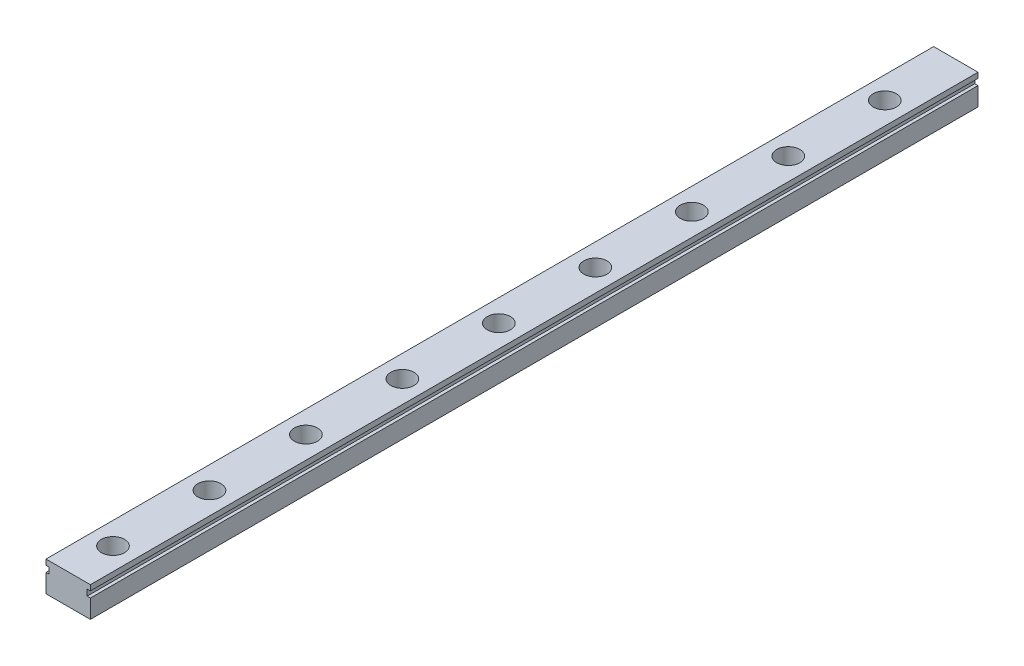
SolidWorks part; units mm, degrees
ref_plane "Front Plane" through (0, 0, 0) normal (0, 0, 1) x (1, 0, 0)
ref_plane "Top Plane" through (0, 0, 0) normal (0, 1, 0) x (1, 0, 0)
ref_plane "Right Plane" through (0, 0, 0) normal (1, 0, 0) x (0, 0, -1)
sketch "Sketch1" plane through (0, 0, 0) normal (0, 0, 1) x (1, 0, 0)
  line L1 (-5.75, -3.9) -> (5.75, -3.9)
  line L2 (-5.75, -3.9) -> (-5.75, 3.9)
  line L3 (-5.75, 3.9) -> (5.75, 3.9)
  line L4 (5.75, -3.9) -> (5.75, 3.9)
  line L5 (-5.75, -3.9) -> (5.75, 3.9) construction
  line L6 (-5.75, 3.9) -> (5.75, -3.9) construction
  point P0 (0, 0)
  dimension "D1" = 11.5
  dimension "D2" = 7.8
extrude "Boss-Extrude1" add sketch "Sketch1" along normal blind 230
sketch "Sketch2" plane through (0, 0, 230) normal (0, 0, 1) x (1, 0, 0)
  line L0 (5.75, -3.9) -> (5.75, 3.9) construction
  line L1 (5.75, 2.5) -> (4.9147, 2.5)
  line L2 (5.75, 2.5) -> (5.75, 0.9)
  line L3 (5.75, 0.9) -> (4.9147, 0.9)
  line L4 (4.9147, 2.5) -> (4.9147, 0.9)
  line L5 (5.75, 3.9) -> (-5.75, 3.9) construction
  line L7 (0, -55) -> (0, 55) construction
  line L8 (-5.75, 0.9) -> (-4.9147, 0.9)
  line L9 (-4.9147, 2.5) -> (-4.9147, 0.9)
  line L10 (-5.75, 2.5) -> (-4.9147, 2.5)
  line L11 (-5.75, 2.5) -> (-5.75, 0.9)
  dimension "D1" = 1.4
  dimension "D2" = 1.6
extrude "Cut-Extrude1" cut sketch "Sketch2" against normal through all
sketch "Sketch3" plane through (0, 3.9, 0) normal (0, 1, 0) x (1, 0, 0)
  line L0 (0, -223.2) -> (0, -215.9183) construction
  line L2 (5.75, -230) -> (-5.75, -230) construction
  circle A0 centre (0, -218.4) radius 3
  circle A1 centre (0, -193.4) radius 3
  circle A2 centre (0, -168.4) radius 3
  circle A3 centre (0, -143.4) radius 3
  circle A4 centre (0, -118.4) radius 3
  circle A5 centre (0, -93.4) radius 3
  circle A6 centre (0, -68.4) radius 3
  circle A7 centre (0, -43.4) radius 3
  circle A8 centre (0, -18.4) radius 3
  circle A9 centre (0, 6.6) radius 3
  circle A10 centre (0, 31.6) radius 3
  circle A11 centre (0, 56.6) radius 3
  circle A12 centre (0, 81.6) radius 3
  circle A13 centre (0, 106.6) radius 3
  circle A14 centre (0, 131.6) radius 3
  circle A15 centre (0, 156.6) radius 3
  circle A16 centre (0, 181.6) radius 3
  circle A17 centre (0, 206.6) radius 3
  circle A18 centre (0, 231.6) radius 3
  circle A19 centre (0, 256.6) radius 3
  circle A20 centre (0, 281.6) radius 3
  circle A21 centre (0, 306.6) radius 3
  circle A22 centre (0, 331.6) radius 3
  circle A23 centre (0, 356.6) radius 3
  circle A24 centre (0, 381.6) radius 3
  dimension "D1" = 11.6
  dimension "D2" = 6
  dimension "D3" = 25
extrude "Cut-Extrude2" cut sketch "Sketch3" against normal blind 4.7
sketch "Sketch4" plane through (0, -0.8, 0) normal (0, 1, 0) x (1, 0, 0)
  circle A0 centre (0, -218.4) radius 1.7
  circle A1 centre (0, -193.4) radius 1.7
  circle A2 centre (0, -168.4) radius 1.7
  circle A3 centre (0, -143.4) radius 1.7
  circle A4 centre (0, -118.4) radius 1.7
  circle A5 centre (0, -93.4) radius 1.7
  circle A6 centre (0, -68.4) radius 1.7
  circle A7 centre (0, -43.4) radius 1.7
  circle A8 centre (0, -18.4) radius 1.7
  circle A9 centre (0, 6.6) radius 1.7
  circle A10 centre (0, 31.6) radius 1.7
  circle A11 centre (0, 56.6) radius 1.7
  circle A12 centre (0, 81.6) radius 1.7
  circle A13 centre (0, 106.6) radius 1.7
  circle A14 centre (0, 131.6) radius 1.7
  circle A15 centre (0, 156.6) radius 1.7
  circle A16 centre (0, 181.6) radius 1.7
  circle A17 centre (0, 206.6) radius 1.7
  circle A18 centre (0, 231.6) radius 1.7
  circle A19 centre (0, 256.6) radius 1.7
  circle A20 centre (0, 281.6) radius 1.7
  circle A21 centre (0, 306.6) radius 1.7
  circle A22 centre (0, 331.6) radius 1.7
  circle A23 centre (0, 356.6) radius 1.7
  circle A24 centre (0, 381.6) radius 1.7
  dimension "D1" = 3.4
  dimension "D2" = 25
extrude "Cut-Extrude3" cut sketch "Sketch4" against normal through all
